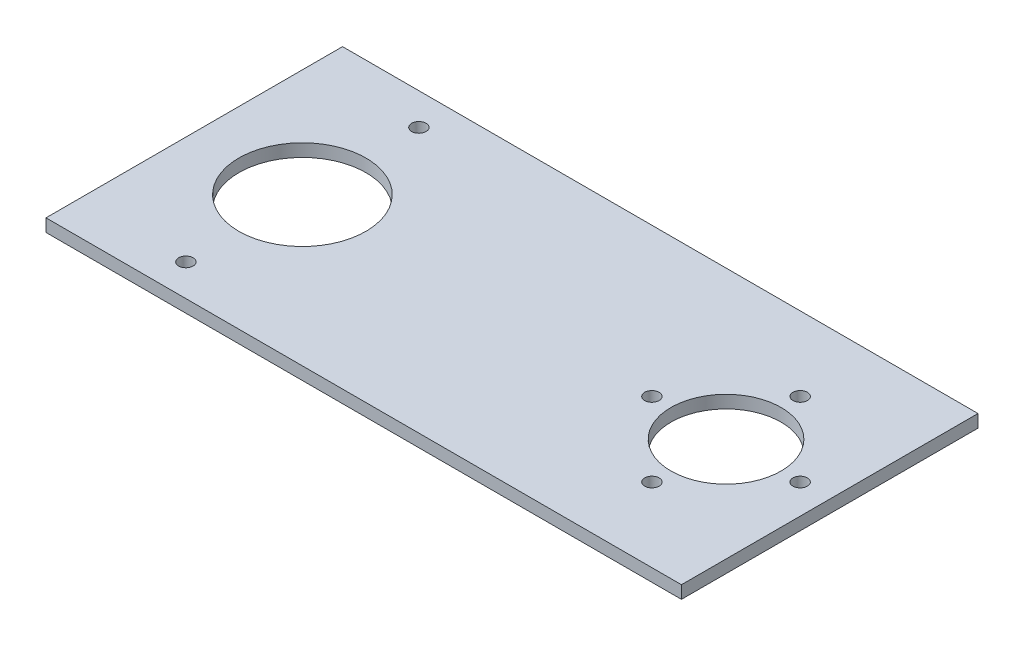
SolidWorks part; units mm, degrees
ref_plane "Front" through (0, 0, 0) normal (0, 0, 1) x (1, 0, 0)
ref_plane "Top" through (0, 0, 0) normal (0, 1, 0) x (1, 0, 0)
ref_plane "Right" through (0, 0, 0) normal (1, 0, 0) x (0, 0, -1)
sketch "Sketch1" plane through (0, 0, 0) normal (0, 1, 0) x (1, 0, 0)
  line L1 (0, 0) -> (150, 0)
  line L2 (0, 0) -> (0, 70)
  line L3 (0, 70) -> (150, 70)
  line L4 (150, 0) -> (150, 70)
  dimension "D1" = 70
  dimension "D2" = 150
extrude "Boss-Extrude1" add sketch "Sketch1" along normal blind 3
sketch "Sketch2" plane through (0, 3, 0) normal (0, 1, 0) x (1, 0, 0)
  line L0 (25.5222, 35) -> (125.5222, 35) construction
  line L1 (51.6438, 45) -> (51.6438, 25) construction
  line L2 (53.6438, 45) -> (53.6438, 25) construction
  line L3 (49.6438, 45) -> (49.6438, 25) construction
  line L4 (25.5222, 70) -> (25.5222, 0) construction
  line L5 (150, 70) -> (0, 70) construction
  line L6 (0, 0) -> (150, 0) construction
  circle A0 centre (25.5222, 35) radius 15
  circle A1 centre (125.5222, 35) radius 13
  arc A2 (53.6438, 45) -> (49.6438, 45) centre (51.6438, 45) ccw construction
  arc A3 (49.6438, 25) -> (53.6438, 25) centre (51.6438, 25) ccw construction
  point P5 (51.6438, 35)
  dimension "D1" = 30
  dimension "D2" = 26
  dimension "D5" = 2
  dimension "D3" = 100
  dimension "D4" = 20
extrude "Cut-Extrude1" cut sketch "Sketch2" against normal through all
hole_wizard "M3 Clearance Hole1" positions "Sketch3" profile "Sketch4" hole size "M3" standard "ISO" end condition through all
sketch "Sketch3" plane through (0, 3, 0) normal (0, 1, 0) x (1, 0, 0)
  line L0 (25.5222, 62.5) -> (25.5222, 7.5) construction
  circle A0 centre (25.5222, 35) radius 15 construction
  circle A1 centre (25.5222, 35) radius 15 construction
  circle A2 centre (125.5222, 35) radius 17.5 construction
  point P0 (25.5222, 62.5)
  point P12 (25.5222, 7.5)
  point P17 (108.0222, 35)
  point P19 (125.5222, 52.5)
  point P21 (143.0222, 35)
  point P23 (125.5222, 17.5)
  dimension "D2" = 35
  dimension "D1" = 55
sketch "Sketch4" plane through (25.5222, 3, -62.5) normal (1, 0, 0) x (0, 0, 1)
  line L0 (0, 0) -> (0, 3)
  line L1 (0, 3) -> (1.7, 3)
  line L2 (1.7, 3) -> (1.7, 0)
  line L5 (1.7, 0) -> (0, 0)
  line L11 (0, -6.35) -> (0, 107.95) construction
  dimension "Thru Hole Dia." = 3.4
  dimension "Thru Hole Depth" = 3
